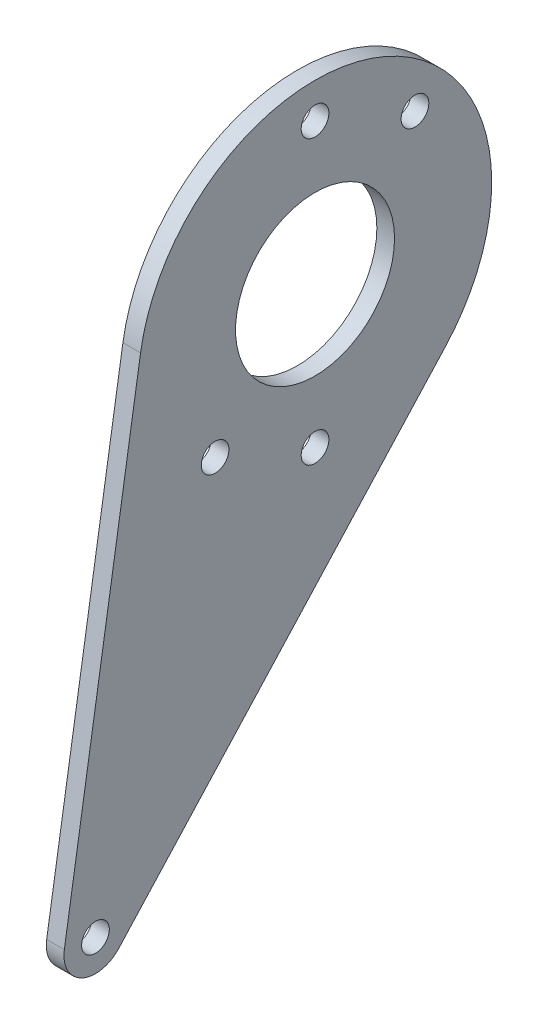
SolidWorks part; units mm, degrees
ref_plane "Front Plane" through (0, 0, 0) normal (1, 0, 0) x (0, 1, 0)
ref_plane "Top Plane" through (0, 0, 0) normal (0, 0, 1) x (0, 1, 0)
ref_plane "Right Plane" through (0, 0, 0) normal (0, 1, 0) x (-1, 0, 0)
sketch "Sketch2" plane through (0, 0, 0) normal (1, 0, 0) x (0, 1, 0)
  line L0 (-29.3267, -4.1835) -> (35.0117, -62.9094)
  line L1 (-24.6174, 5.5937) -> (61.4089, -8.1042)
  circle A0 centre (56.4162, -39.4592) radius 25.4 construction
  circle A1 centre (56.4162, -39.4592) radius 14.2875
  circle A2 centre (-25.5081, 0) radius 2.4892
  arc A3 (-24.6174, 5.5937) -> (-29.3267, -4.1835) centre (-25.5081, 0) ccw
  arc A4 (35.0117, -62.9094) -> (61.4089, -8.1042) centre (56.4162, -39.4592) ccw
  point P0 (-25.5081, 0)
  point P1 (74.5679, 0)
  point P2 (56.4162, -39.4592)
  point P5 (31.0162, -39.4592)
  point P6 (38.4557, -21.4987)
  point P7 (81.8162, -39.4592)
  point P10 (74.3767, -57.4197)
  dimension "D4" = 50.8
  dimension "D7" = 28.575
  dimension "D8" = 4.9784
  dimension "D9" = 3.175
  dimension "D10" = 6.35
  dimension "D1" = 100.076
  dimension "D2" = 43.434
  dimension "D3" = 90.932
  dimension "D5" = 45
  dimension "D6" = 2
extrude "Boss-Extrude1" add sketch "Sketch2" along normal blind 3.175
sketch "Sketch3" plane through (3.175, 0, 0) normal (1, 0, 0) x (0, 1, 0)
  line L2 (61.4089, -8.1042) -> (-24.6174, 5.5937)
  line L3 (-29.3267, -4.1835) -> (35.0117, -62.9094)
  line L4 (61.4089, -8.1042) -> (-24.6174, 5.5937)
  line L5 (-29.3267, -4.1835) -> (35.0117, -62.9094)
  circle A1 centre (-25.5081, 0) radius 2.4892
  circle A2 centre (-25.5081, 0) radius 2.4892
  circle A3 centre (56.4162, -39.4592) radius 14.2875
  circle A4 centre (56.4162, -39.4592) radius 14.2875
  arc A6 (35.0117, -62.9094) -> (61.4089, -8.1042) centre (56.4162, -39.4592) ccw
  arc A7 (-24.6174, 5.5937) -> (-29.3267, -4.1835) centre (-25.5081, 0) ccw
  arc A8 (35.0117, -62.9094) -> (61.4089, -8.1042) centre (56.4162, -39.4592) ccw
  arc A9 (-24.6174, 5.5937) -> (-29.3267, -4.1835) centre (-25.5081, 0) ccw
  point P8 (74.3767, -57.4197)
  point P13 (31.0162, -39.4592)
  point P14 (38.4557, -21.4987)
  point P15 (81.8162, -39.4592)
  dimension "D1" = 0
  dimension "D2" = 0
  dimension "D3" = 0
hole_wizard "#9 (0.196) Diameter Hole1" positions "Sketch3" profile "Sketch4" hole size "#9" standard "ANSI Inch" end condition through all
sketch "Sketch4" plane through (3.175, 81.8162, -39.4592) normal (0, 1, 0) x (0, 0, -1)
  line L0 (0, 0) -> (0, 3.175)
  line L1 (0, 3.175) -> (2.4892, 3.175)
  line L2 (2.4892, 3.175) -> (2.4892, 0)
  line L5 (2.4892, 0) -> (0, 0)
  line L11 (0, -6.35) -> (0, 107.95) construction
  dimension "Thru Hole Dia." = 4.9784
  dimension "Thru Hole Depth" = 3.175
